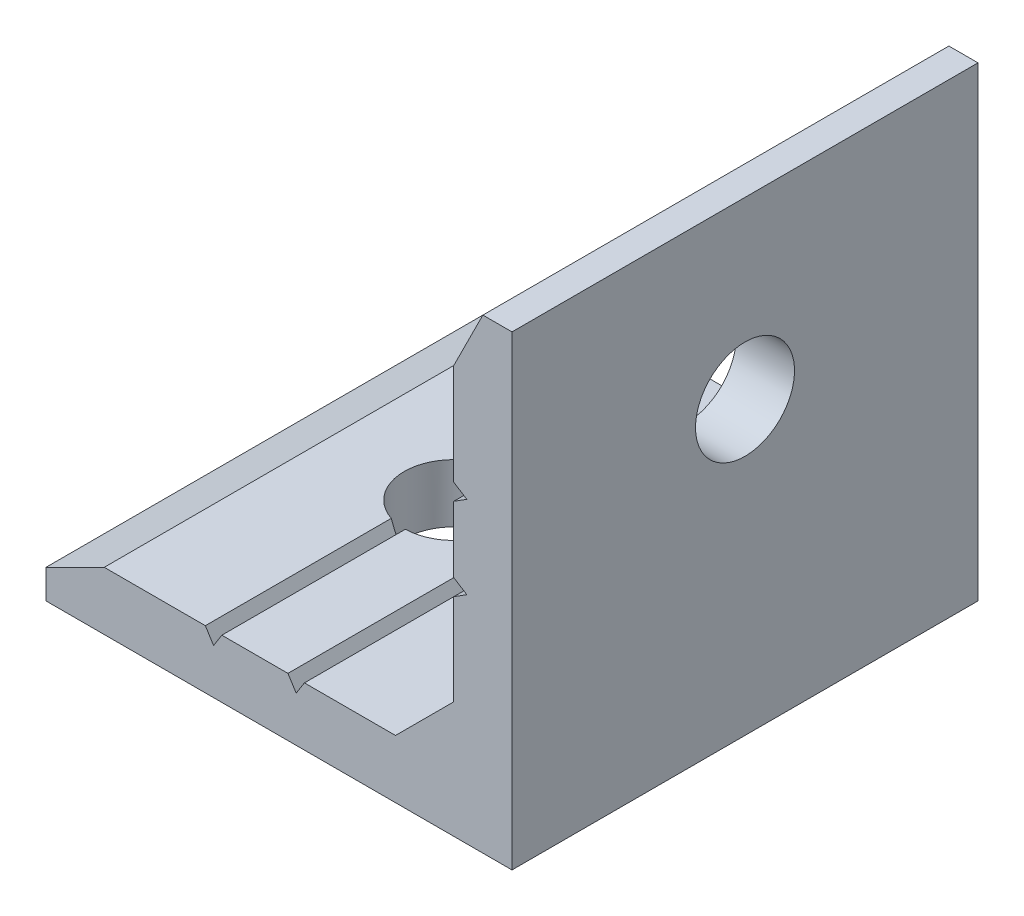
SolidWorks part; units mm, degrees
ref_plane "前视基准面" through (0, 0, 0) normal (0, 0, 1) x (1, 0, 0)
ref_plane "上视基准面" through (0, 0, 0) normal (0, 1, 0) x (1, 0, 0)
ref_plane "右视基准面" through (0, 0, 0) normal (1, 0, 0) x (0, 0, -1)
sketch "草图1" plane through (0, 0, 0) normal (0, 0, 1) x (1, 0, 0)
  line B0 (0, 0) -> (40, 0)
  line B1 (40, 0) -> (40, 40)
  line B2 (0, 0) -> (0, 2.5)
  line B3 (0, 2.5) -> (5, 5)
  line B4 (5, 5) -> (13.6775, 5)
  line B5 (15.0945, 5) -> (20.7667, 5)
  line B6 (22.1836, 5) -> (35, 5)
  line B7 (35, 5) -> (35, 17.8164)
  line B8 (35, 19.2333) -> (35, 24.9055)
  line B9 (35, 26.3225) -> (35, 35)
  line B10 (35, 35) -> (37.5, 40)
  line B11 (37.5, 40) -> (40, 40)
  line B12 (14.386, 3.8797) -> (13.6775, 5)
  line B13 (14.386, 3.8797) -> (15.0945, 5)
  line B14 (21.4751, 3.8797) -> (20.7667, 5)
  line B15 (21.4751, 3.8797) -> (22.1836, 5)
  line B16 (36.1203, 25.614) -> (35, 26.3225)
  line B17 (36.1203, 25.614) -> (35, 24.9055)
  line B18 (36.1203, 18.5249) -> (35, 19.2333)
  line B19 (36.1203, 18.5249) -> (35, 17.8164)
sketch_block_instance "A$C16494831-1"
sketch_block "A$C16494831"
extrude "凸台-拉伸1" add sketch "草图1" along normal blind 40
chamfer "倒角1" distance 5 angle 45 1 edges at (35, 5, 20)
sketch "草图3" plane through (0, 5, 0) normal (0, 1, 0) x (1, 0, 0)
  line L0 (40, -40) -> (40, 0) construction
  circle A0 centre (15, -20) radius 4.25
  dimension "D1" = 25
extrude "切除-拉伸1" cut sketch "草图3" against normal through all
sketch "草图4" plane through (35, 0, 0) normal (-1, 0, 0) x (0, 0, 1)
  line L0 (40, 0) -> (0, 0) construction
  circle A0 centre (20, 25) radius 4.25
  dimension "D1" = 25
extrude "切除-拉伸2" cut sketch "草图4" against normal blind 40
